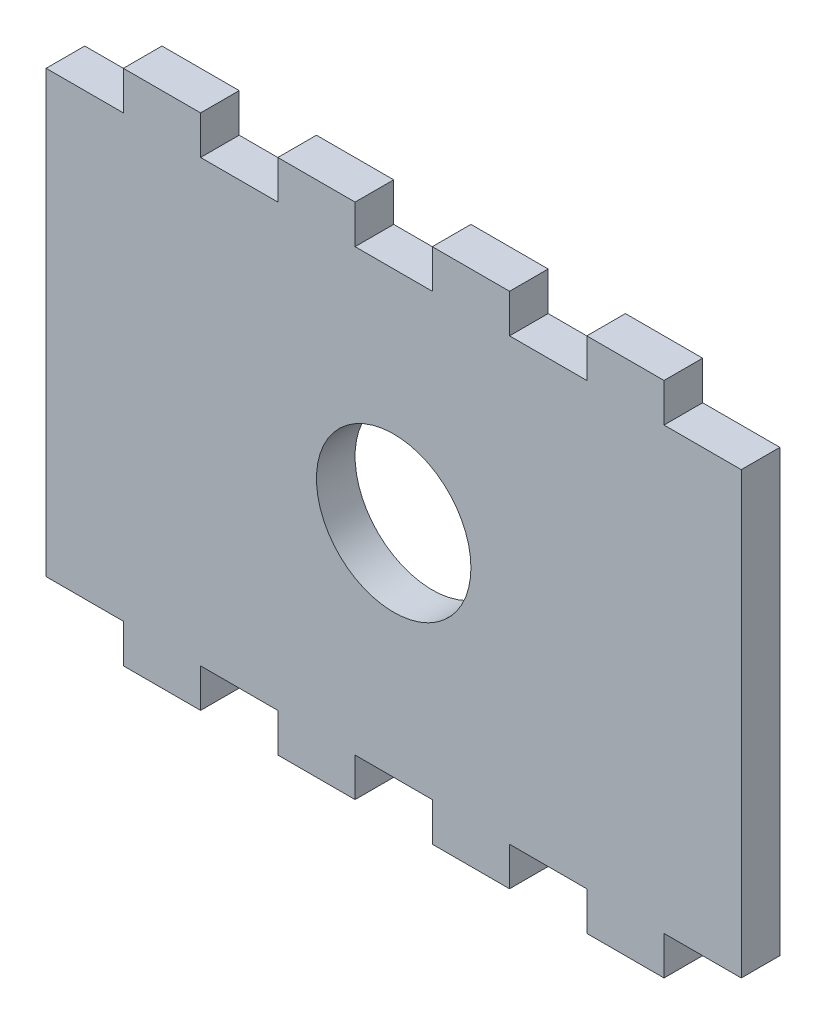
SolidWorks part; units mm, degrees
material "Acrylic (Medium-high impact)"
ref_plane "Front Plane" through (0, 0, 0) normal (0, 0, 1) x (1, 0, 0)
ref_plane "Top Plane" through (0, 0, 0) normal (0, 1, 0) x (1, 0, 0)
ref_plane "Right Plane" through (0, 0, 0) normal (1, 0, 0) x (0, 0, -1)
sketch "Sketch1" plane through (0, 0, 0) normal (0, 0, 1) x (1, 0, 0)
  line L0 (6.35, 0) -> (6.35, -3.175)
  line L1 (0, 0) -> (6.35, 0)
  line L2 (0, 0) -> (0, 36.195)
  line L3 (0, 36.195) -> (6.35, 36.195)
  line L4 (57.15, 0) -> (57.15, 36.195)
  line L5 (6.35, -3.175) -> (12.7, -3.175)
  line L6 (12.7, -3.175) -> (12.7, 0)
  line L7 (19.05, 0) -> (19.05, -3.175)
  line L8 (19.05, -3.175) -> (25.4, -3.175)
  line L9 (25.4, -3.175) -> (25.4, 0)
  line L10 (31.75, 0) -> (31.75, -3.175)
  line L11 (31.75, -3.175) -> (38.1, -3.175)
  line L12 (38.1, -3.175) -> (38.1, 0)
  line L13 (44.45, 0) -> (44.45, -3.175)
  line L14 (44.45, -3.175) -> (50.8, -3.175)
  line L15 (50.8, -3.175) -> (50.8, 0)
  line L16 (12.7, 0) -> (19.05, 0)
  line L17 (25.4, 0) -> (31.75, 0)
  line L18 (38.1, 0) -> (44.45, 0)
  line L19 (50.8, 0) -> (57.15, 0)
  line L20 (0, 18.0975) -> (57.15, 18.0975) construction
  line L21 (50.8, 39.37) -> (50.8, 36.195)
  line L22 (44.45, 39.37) -> (50.8, 39.37)
  line L23 (44.45, 36.195) -> (44.45, 39.37)
  line L24 (38.1, 39.37) -> (38.1, 36.195)
  line L25 (31.75, 39.37) -> (38.1, 39.37)
  line L26 (31.75, 36.195) -> (31.75, 39.37)
  line L27 (25.4, 39.37) -> (25.4, 36.195)
  line L28 (19.05, 39.37) -> (25.4, 39.37)
  line L29 (19.05, 36.195) -> (19.05, 39.37)
  line L30 (12.7, 39.37) -> (12.7, 36.195)
  line L31 (6.35, 39.37) -> (12.7, 39.37)
  line L32 (6.35, 36.195) -> (6.35, 39.37)
  line L33 (12.7, 36.195) -> (19.05, 36.195)
  line L34 (25.4, 36.195) -> (31.75, 36.195)
  line L35 (38.1, 36.195) -> (44.45, 36.195)
  line L36 (50.8, 36.195) -> (57.15, 36.195)
  line L37 (28.575, 36.195) -> (28.575, 0) construction
  circle A0 centre (28.575, 18.0975) radius 6.35
  dimension "D7" = 12.7
  dimension "D1" = 6.35
  dimension "D2" = 3.175
  dimension "D4" = 6.35
  dimension "D5" = 6.35
  dimension "D6" = 36.195
  dimension "D3" = 4
extrude "Boss-Extrude1" add sketch "Sketch1" along normal blind 3.175
